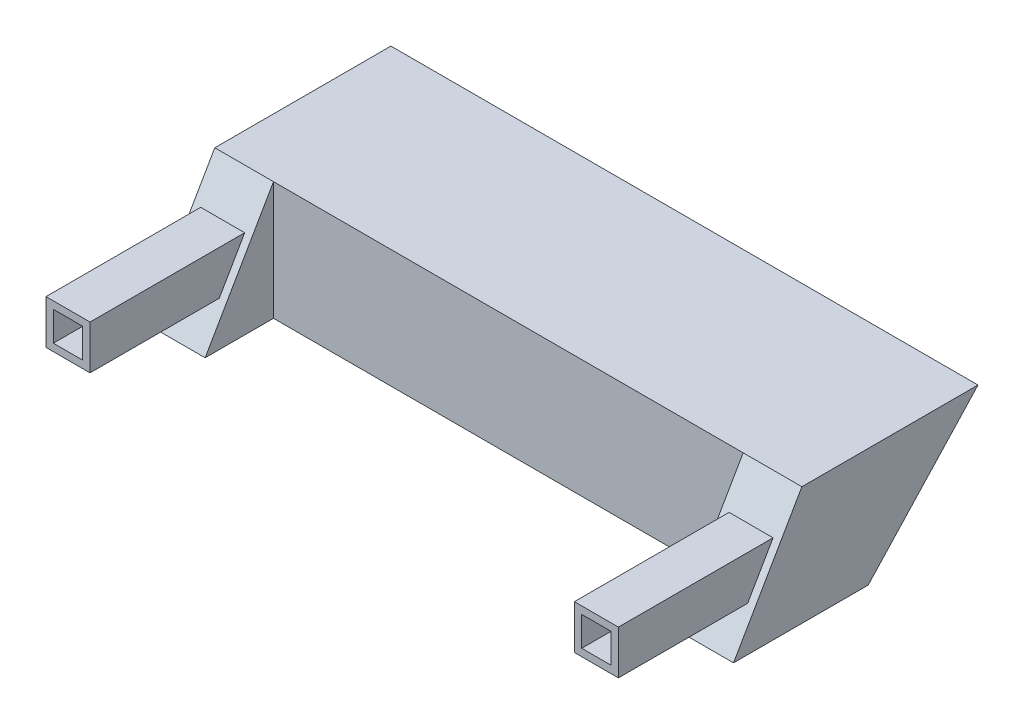
SolidWorks part; units mm, degrees
ref_plane "Front Plane" through (0, 0, 0) normal (0, 0, 1) x (1, 0, 0)
ref_plane "Top Plane" through (0, 0, 0) normal (0, 1, 0) x (1, 0, 0)
ref_plane "Right Plane" through (0, 0, 0) normal (1, 0, 0) x (0, 0, -1)
sketch "Sketch1" plane through (0, 0, 0) normal (1, 0, 0) x (0, 0, -1)
  line L0 (0, 0) -> (0, 51.2149)
  line L1 (0, 51.2149) -> (76.2, 51.2149)
  line L2 (76.2, 51.2149) -> (28.702, 0)
  line L3 (28.702, 0) -> (0, 0)
  dimension "D1" = 28.702
  dimension "D2" = 69.85
  dimension "D3" = 76.2
extrude "Boss-Extrude1" add sketch "Sketch1" along normal mid plane 254
sketch "Sketch3" plane through (0, 0, 0) normal (1, 0, 0) x (0, 0, -1)
  line L0 (0, 51.2149) -> (-29.5689, 0)
  line L1 (0, 28.1682) -> (0, -28.1682) construction
  line L2 (76.2, 51.2149) -> (0, 51.2149) construction
  line L3 (41.91, 0) -> (-41.91, 0) construction
  line L4 (-29.5689, 0) -> (0, 0)
  line L5 (0, 51.2149) -> (0, 0)
  dimension "D1" = 60
  dimension "D2" = 105.7689
extrude "Boss-Extrude2" add sketch "Sketch3" along normal blind 25.4 from offset 101.6
mirror "Mirror1" about plane through (0, 0, 0) normal (1, 0, 0) of "Boss-Extrude2"
sketch "Sketch4" plane through (0, 0, 0) normal (0, 0, 1) x (1, 0, 0)
  line L0 (101.6, 51.2149) -> (127, 51.2149) construction
  line L1 (104.775, 35.1324) -> (123.825, 35.1324)
  line L2 (104.775, 35.1324) -> (104.775, 16.0824)
  line L3 (104.775, 16.0824) -> (123.825, 16.0824)
  line L4 (123.825, 35.1324) -> (123.825, 16.0824)
  line L5 (107.95, 31.9574) -> (120.65, 31.9574)
  line L6 (107.95, 31.9574) -> (107.95, 19.2574)
  line L7 (107.95, 19.2574) -> (120.65, 19.2574)
  line L8 (120.65, 31.9574) -> (120.65, 19.2574)
  line L9 (101.6, 51.2149) -> (101.6, 0) construction
  point P8 (114.3, 19.2574)
  point P9 (114.3, 16.0824)
  point P10 (120.65, 25.6074)
  point P11 (123.825, 25.6074)
  point P12 (114.3, 51.2149)
  point P17 (114.3, 35.1324)
  point P18 (101.6, 25.6074)
  point P21 (107.95, 25.6074)
  dimension "D1" = 19.05
  dimension "D2" = 12.7
extrude "Boss-Extrude3" add sketch "Sketch4" along normal blind 76.2
mirror "Mirror2" about plane through (0, 0, 0) normal (1, 0, 0) of "Boss-Extrude3"
equation "\"height\"= 2in"
equation "\"top length\"= 3in"
equation "\"bottom length\"= 1.13in"
equation "\"diag face\"= 2.75in"
equation "\"interface diag\"= 2.25in"
equation "\"D1@Sketch1\"=\"bottom length\""
equation "\"D2@Sketch1\"=\"diag face\""
equation "\"D3@Sketch1\"=\"top length\""
equation "\"width\"= 10in"
equation "\"D1@Boss-Extrude1\"=\"width\""
equation "\"interfacewidth\"= 1in"
equation "\"D19@Boss-Extrude2\"=\"width\"/2  - \"interfacewidth\""
equation "\"D1@Boss-Extrude2\"=\"interfacewidth\""
equation "\"Connector OD\"= .75in"
equation "\"Connector ID\"= .5in"
equation "\"D1@Sketch4\"=\"Connector OD\""
equation "\"D2@Sketch4\"=\"Connector ID\""
equation "\"Connector Length\"= 3in"
equation "\"D1@Boss-Extrude3\"=\"Connector Length\""
